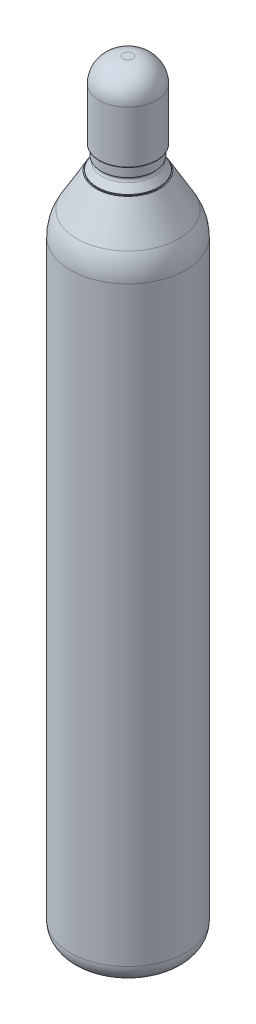
SolidWorks part; units mm, degrees
ref_plane "前视基准面" through (0, 0, 0) normal (0, 0, 1) x (1, 0, 0)
ref_plane "上视基准面" through (0, 0, 0) normal (0, 1, 0) x (1, 0, 0)
ref_plane "右视基准面" through (0, 0, 0) normal (1, 0, 0) x (0, 0, -1)
sketch "草图1" plane through (0, 0, 0) normal (0, 0, 1) x (1, 0, 0)
  line L0 (0, 0) -> (0, -131.9067) construction
  line L1 (0, 0) -> (-40, 0)
  line L2 (-60, 20) -> (-60, 636.6025)
  line L3 (-53.3013, 661.6025) -> (-33.094, 696.6025)
  line L4 (-30, 721) -> (-30, 775)
  line L5 (-5, 800) -> (0, 800)
  line L6 (0, 5) -> (-40, 5)
  line L7 (-29, 720) -> (-28.9, 720)
  line L8 (-28, 719.1) -> (-28, 710)
  line L9 (-28, 710) -> (-26, 710)
  line L10 (-26, 710) -> (-26, 707.6231)
  line L11 (-32.094, 697.6025) -> (-32.094, 696.6025)
  line L12 (-33.094, 696.6025) -> (-32.094, 696.6025)
  line L13 (-26.9533, 704.6864) -> (-32.094, 697.6025)
  line L14 (-55, 20) -> (-55, 636.6025)
  line L15 (-48.9711, 659.1025) -> (-30.2073, 691.6025)
  line L16 (-30.2073, 691.6025) -> (-27.094, 691.6025)
  line L17 (-27.094, 695.9795) -> (-27.094, 691.6025)
  line L18 (-21, 704.3769) -> (-27.094, 695.9795)
  line L19 (-21, 715) -> (-21, 704.3769)
  line L20 (-23, 715) -> (-21, 715)
  line L21 (-23, 725) -> (-23, 715)
  line L22 (-25, 725) -> (-23, 725)
  line L23 (-25, 725) -> (-25, 775)
  line L24 (-5, 795) -> (0, 795)
  line L25 (0, 800) -> (0, 795)
  line L26 (0, 5) -> (0, 0)
  line L27 (-30, 720) -> (-28, 720) construction
  line L28 (-30, 720) -> (-30, 775) construction
  line L29 (-28, 720) -> (-28, 710) construction
  line L30 (-26, 710) -> (-26, 706) construction
  line L31 (-26, 706) -> (-32.094, 697.6025) construction
  arc A0 (-60, 20) -> (-40, 0) centre (-40, 20) ccw
  arc A1 (-60, 636.6025) -> (-53.3013, 661.6025) centre (-10, 636.6025) cw
  arc A2 (-55, 20) -> (-40, 5) centre (-40, 20) ccw
  arc A3 (-30, 775) -> (-5, 800) centre (-5, 775) cw
  arc A4 (-55, 636.6025) -> (-48.9711, 659.1025) centre (-10, 636.6025) cw
  arc A5 (-25, 775) -> (-5, 795) centre (-5, 775) cw
  arc A6 (-29, 720) -> (-30, 721) centre (-29, 721) cw
  arc A7 (-28, 719.1) -> (-28.9, 720) centre (-28.9, 719.1) ccw
  arc A8 (-26, 707.6231) -> (-26.9533, 704.6864) centre (-31, 707.6231) cw
  point P10 (-60, 0)
  point P13 (-60, 650)
  point P19 (-30, 800)
  point P46 (-30, 720)
  point P53 (-26, 706)
  dimension "D6" = 20
  dimension "D7" = 50
  dimension "D9" = 25
  dimension "D18" = 1
  dimension "D19" = 0.9
  dimension "D4" = 5
  dimension "D1" = 650
  dimension "D2" = 60
  dimension "D3" = 800
  dimension "D5" = 30
  dimension "D10" = 2
  dimension "D11" = 4
  dimension "D12" = 1
  dimension "D13" = 1
  dimension "D14" = 80
  dimension "D15" = 60
  dimension "D16" = 60
  dimension "D17" = 5
revolve "旋转1" add sketch "草图1" angle 360 about L0
